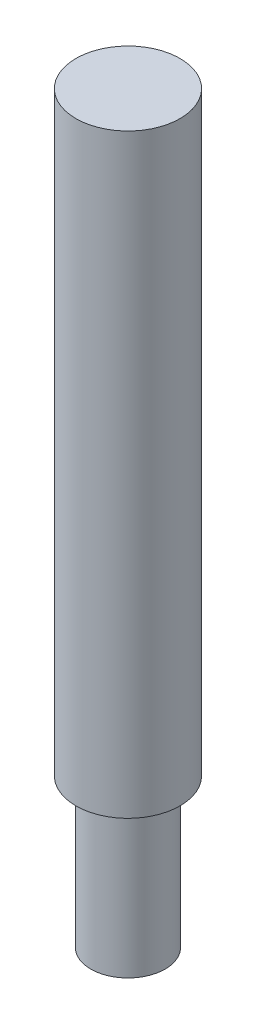
SolidWorks part; units mm, degrees
ref_plane "Front Plane" through (0, 0, 0) normal (0, 0, 1) x (1, 0, 0)
ref_plane "Top Plane" through (0, 0, 0) normal (0, 1, 0) x (1, 0, 0)
ref_plane "Right Plane" through (0, 0, 0) normal (1, 0, 0) x (0, 0, -1)
sketch "Sketch1" plane through (0, 0, 0) normal (0, 1, 0) x (1, 0, 0)
  circle A0 centre (0, 0) radius 2.5
  dimension "D1" = 5
extrude "Boss-Extrude1" add sketch "Sketch1" along normal blind 10
sketch "Sketch2" plane through (0, 10, 0) normal (0, 1, 0) x (1, 0, 0)
  circle A0 centre (0, 0) radius 3.5
  dimension "D1" = 7
extrude "Boss-Extrude2" add sketch "Sketch2" along normal blind 40
